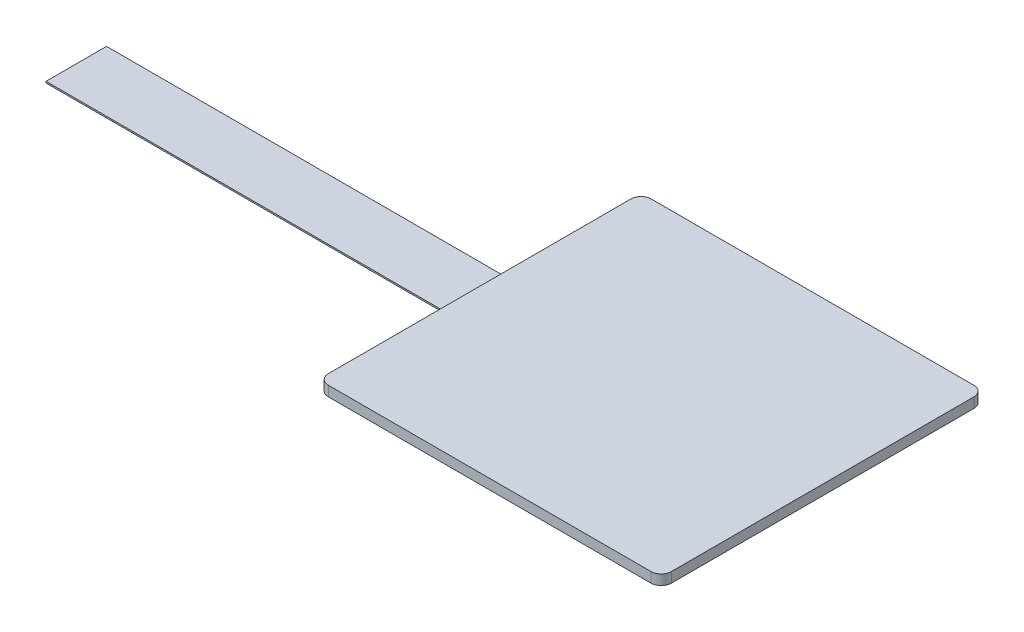
SolidWorks part; units mm, degrees
ref_plane "前基準面" through (0, 0, 0) normal (0, 0, 1) x (1, 0, 0)
ref_plane "上基準面" through (0, 0, 0) normal (0, 1, 0) x (1, 0, 0)
ref_plane "右基準面" through (0, 0, 0) normal (1, 0, 0) x (0, 0, -1)
sketch "草圖1" plane through (0, 0, 0) normal (0, 1, 0) x (1, 0, 0)
  line L1 (17, -16) -> (-17, -16)
  line L2 (17, -16) -> (17, 16)
  line L3 (17, 16) -> (-17, 16)
  line L4 (-17, -16) -> (-17, 16)
  line L6 (-57, 3) -> (-57, -3) construction
  line L7 (-57, -3) -> (-17, -3) construction
  line L8 (-17, 3) -> (-17, -3)
  dimension "D1" = 34
  dimension "D2" = 32
  dimension "D3" = 17
  dimension "D4" = 16
  dimension "D5" = 6
  dimension "D6" = 3
  dimension "D7" = 40
extrude "填料-伸長1" add sketch "草圖1" along normal blind 1 contours L4 L1 L2 L3
sketch "草圖2" plane through (0, 0, 0) normal (0, 1, 0) x (1, 0, 0)
  line L1 (-57, 3) -> (-17, 3)
  line L2 (-57, 3) -> (-57, -3)
  line L3 (-57, -3) -> (-17, -3)
  line L4 (-17, 3) -> (-17, -3)
extrude "填料-伸長2" add sketch "草圖2" along normal blind 0.1 and the other way blind 0.05
fillet "圓角1" radius 1 4 edges at (-17, 0.5, 16) (17, 0.5, 16) (17, 0.5, -16) (-17, 0.5, -16)
